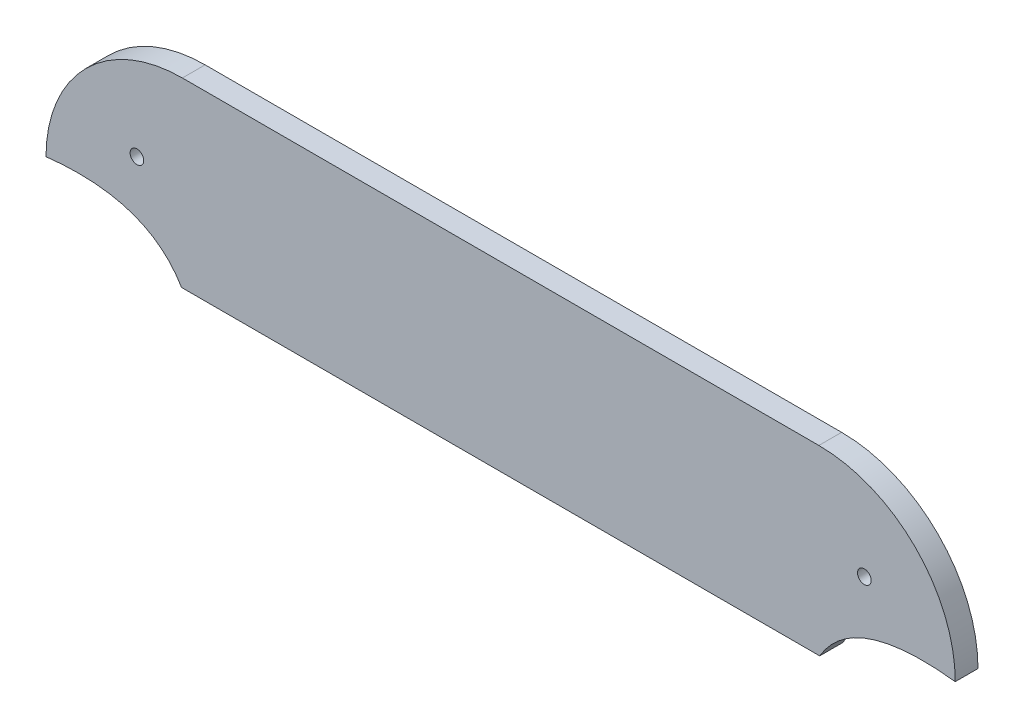
SolidWorks part; units mm, degrees
ref_plane "Front Plane" through (0, 0, 0) normal (0, 0, 1) x (1, 0, 0)
ref_plane "Top Plane" through (0, 0, 0) normal (0, 1, 0) x (1, 0, 0)
ref_plane "Right Plane" through (0, 0, 0) normal (1, 0, 0) x (0, 0, -1)
sketch "Sketch1" plane through (0, 0, 0) normal (0, 0, 1) x (1, 0, 0)
  line L1 (-90, -100) -> (90, -100)
  line L2 (-100, -90) -> (-100, 70)
  line L3 (-70, 100) -> (70, 100)
  line L4 (100, -90) -> (100, 70)
  arc A0 (90, -100) -> (100, -90) centre (90, -90) ccw
  arc A1 (-90, -100) -> (-100, -90) centre (-90, -90) cw
  arc A2 (70, 100) -> (100, 70) centre (70, 70) cw
  arc A3 (-100, 70) -> (-70, 100) centre (-70, 70) cw
  point P0 (0, 0)
  point P16 (100, -100)
  point P19 (-100, -100)
  point P23 (100, 100)
  point P26 (-100, 100)
  dimension "D6" = 10
  dimension "D7" = 10
  dimension "D8" = 30
  dimension "D9" = 30
  dimension "D1" = 200
  dimension "D2" = 200
  dimension "D10" = 100
  dimension "D11" = 100
extrude "Boss-Extrude1" add sketch "Sketch1" along normal blind 5
sketch "Sketch2" plane through (0, 0, 5) normal (0, 0, 1) x (1, 0, 0)
  line L0 (100, -20) -> (70, -20)
  line L1 (100, -90) -> (100, 70) construction
  line L2 (70, -20) -> (70, -90)
  line L3 (70, -90) -> (100, -90)
  line L4 (100, -90) -> (100, -20)
  line L5 (0, 100) -> (0, -100) construction
  line L6 (70, 100) -> (-70, 100) construction
  line L7 (-90, -100) -> (90, -100) construction
  line L8 (-70, -90) -> (-100, -90)
  line L9 (-70, -20) -> (-70, -90)
  line L10 (-100, -20) -> (-70, -20)
  line L11 (-100, -90) -> (-100, -20)
  dimension "D1" = 70
  dimension "D2" = 30
  dimension "D3" = 10
extrude "Cut-Extrude1" cut sketch "Sketch2" against normal blind 5
sketch "Sketch3" plane through (0, 0, 5) normal (0, 0, 1) x (1, 0, 0)
  line L0 (100, -20) -> (70, -20) construction
  line L1 (85, -20) -> (100, -20)
  line L2 (100, -20) -> (100, 70)
  line L3 (0, 100) -> (0, -100) construction
  line L4 (70, 100) -> (-70, 100) construction
  line L5 (-90, -100) -> (90, -100) construction
  line L6 (-85, -20) -> (-100, -20)
  line L7 (-100, -20) -> (-100, 70)
  spline S0 degree 2 poles (100, 70) (41.5628, 76.7696) (85, -20) knots 0 0 0 1 1 1
  spline S1 degree 2 poles (-100, 70) (-41.5628, 76.7696) (-85, -20) knots 0 0 0 1 1 1
extrude "Cut-Extrude2" cut sketch "Sketch3" against normal blind 5
sketch "Sketch5" plane through (0, 0, 5) normal (0, 0, 1) x (1, 0, 0)
  line L0 (-90, -100) -> (90, -100) construction
  line L1 (70, -20) -> (70, -90) construction
  line L2 (-70, -90) -> (-70, -20) construction
  line L3 (-50, -50) -> (34.8101, -50) construction
  circle A0 centre (50, -80) radius 2.5
  circle A1 centre (-50, -80) radius 2.5
  circle A2 centre (50, -20) radius 2.5
  circle A3 centre (-50, -20) radius 2.5
  dimension "D3" = 20
  dimension "D5" = 5
  dimension "D6" = 5
  dimension "D1" = 20
  dimension "D2" = 20
  dimension "D4" = 20
  dimension "D7" = 30
extrude "Cut-Extrude3" cut sketch "Sketch5" against normal blind 5
sketch "Sketch6" plane through (0, 0, 5) normal (0, 0, 1) x (1, 0, 0)
  line L0 (-90, -100) -> (90, -100) construction
  circle A0 centre (0, -90) radius 2.5
  dimension "D2" = 5
  dimension "D1" = 10
extrude "Cut-Extrude4" cut sketch "Sketch6" against normal blind 5
sketch "Sketch7" plane through (0, 0, 5) normal (0, 0, 1) x (1, 0, 0)
  line L0 (-70.1824, 60) -> (70.1824, 60)
  line L1 (70, 100) -> (-70, 100) construction
  line L2 (-141.9149, 60) -> (-70.1824, 60)
  line L3 (70.1824, 60) -> (160.1347, 60)
  line L4 (160.1347, 60) -> (160.1347, -117.0755)
  line L5 (160.1347, -117.0755) -> (-141.9149, -117.0755)
  line L6 (-141.9149, -117.0755) -> (-141.9149, 60)
  parabola Q0 (-85, -20) -> (-100, 70) focus (-79.8499, 57.287) apex (-73.2729, 63.9714) construction
  parabola Q1 (100, 70) -> (85, -20) focus (79.8499, 57.287) apex (73.2729, 63.9714) construction
  dimension "D1" = 40
extrude "Cut-Extrude5" cut sketch "Sketch7" against normal blind 5
sketch "Sketch8" plane through (0, 0, 5) normal (0, 0, 1) x (1, 0, 0)
  line L0 (70, 100) -> (-70, 100) construction
  circle A0 centre (-80, 80) radius 1.5
  circle A1 centre (80, 80) radius 1.5
  dimension "D1" = 20
  dimension "D3" = 3
  dimension "D4" = 20
  dimension "D6" = 3
  dimension "D2" = 20
  dimension "D5" = 20
extrude "Cut-Extrude6" cut sketch "Sketch8" against normal blind 5
